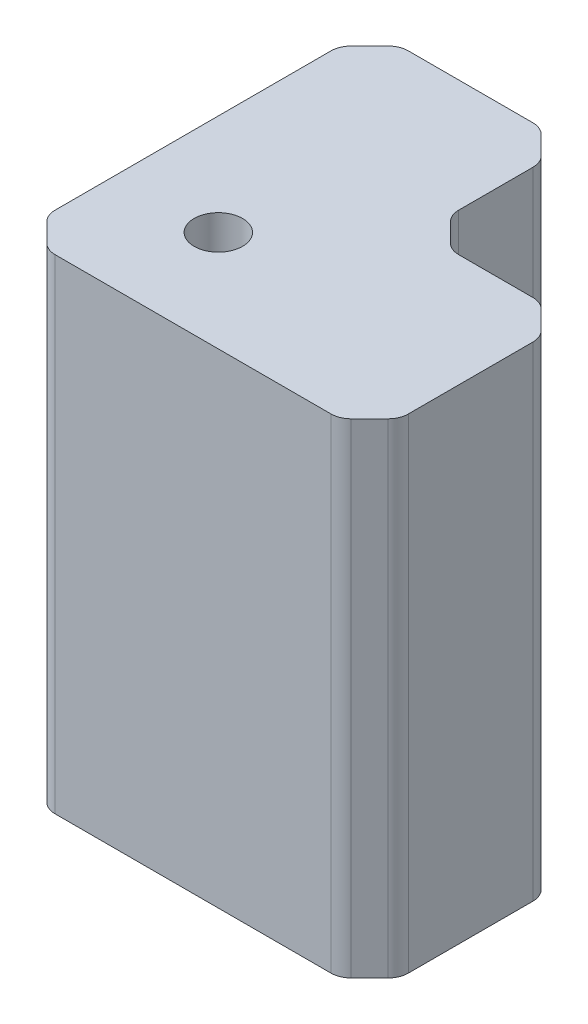
SolidWorks part; units mm, degrees
ref_plane "Front Plane" through (0, 0, 0) normal (0, 0, 1) x (1, 0, 0)
ref_plane "Top Plane" through (0, 0, 0) normal (0, 1, 0) x (1, 0, 0)
ref_plane "Right Plane" through (0, 0, 0) normal (1, 0, 0) x (0, 0, -1)
sketch "Sketch1" plane through (0, 0, 0) normal (0, 1, 0) x (1, 0, 0)
  line L0 (-10, 10) -> (-10, 25)
  line L2 (-10, 10) -> (-10, -10)
  line L3 (-10, -10) -> (10, -10)
  line L5 (0, -10) -> (0, 25) construction
  line L6 (-10, 0) -> (25, 0) construction
  line L7 (-10, 25) -> (10, 25)
  line L8 (10, 25) -> (10, 10)
  line L9 (25, 10) -> (25, -10)
  line L10 (25, -10) -> (10, -10)
  line L11 (10, 10) -> (25, 10)
  point P8 (0, 26.4591)
  point P9 (23.9241, 0)
  point P60 (0, 0)
  dimension "D1" = 20
  dimension "D2" = 20
  dimension "D3" = 15
  dimension "D4" = 15
extrude "Boss-Extrude1" add sketch "Sketch1" along normal blind 48
sketch "Sketch2" plane through (0, 48, 0) normal (0, 1, 0) x (1, 0, 0)
  point P0 (0, 0)
hole_wizard "M4 Clearance Hole1" positions "Sketch2" profile "Sketch3" hole size "M4" standard "ISO" end condition up to next
sketch "Sketch3" plane through (0, 48, 0) normal (1, 0, 0) x (0, 0, 1)
  line L0 (0, 0) -> (0, 48)
  line L1 (0, 48) -> (2.4, 48)
  line L2 (2.4, 48) -> (2.4, 0)
  line L5 (2.4, 0) -> (0, 0)
  line L11 (0, -6.35) -> (0, 107.95) construction
  dimension "Thru Hole Dia." = 4.8
  dimension "Thru Hole Depth" = 48
sketch "Sketch4" plane through (0, 0, 0) normal (0, -1, 0) x (1, 0, 0)
  circle A0 centre (0, 0) radius 5
  dimension "D1" = 10
extrude "Cut-Extrude1" cut sketch "Sketch4" against normal blind 2
chamfer "Chamfer1" distance 3 angle 45 6 edges at (10, 24, -10) (-10, 24, -25) (10, 24, -25) (25, 24, -10) (25, 24, 10) (-10, 24, 10)
fillet "Fillet1" radius 2 12 edges at (-10, 24, 7) (-7, 24, 10) (22, 24, 10) (25, 24, 7) (25, 24, -7) (22, 24, -10) (13, 24, -10) (10, 24, -13) (7, 24, -25) (-7, 24, -25) (-10, 24, -22) (10, 24, -22)
